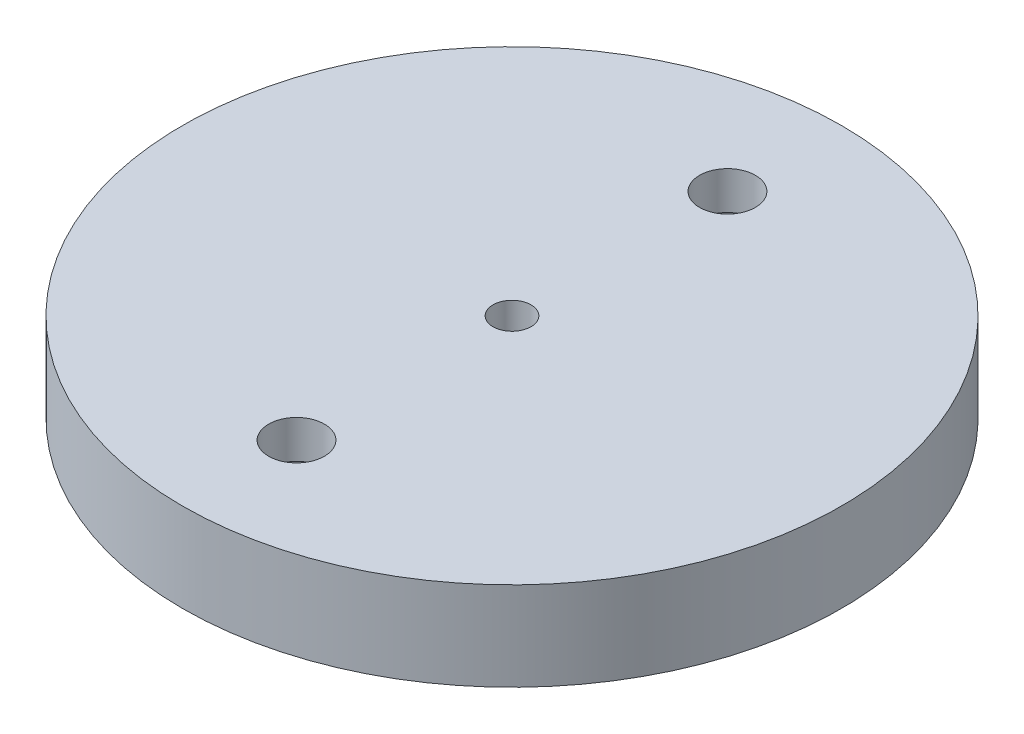
SolidWorks part; units mm, degrees
material "ABS"
ref_plane "Front Plane" through (0, 0, 0) normal (0, 0, 1) x (1, 0, 0)
ref_plane "Top Plane" through (0, 0, 0) normal (0, 1, 0) x (1, 0, 0)
ref_plane "Right Plane" through (0, 0, 0) normal (1, 0, 0) x (0, 0, -1)
sketch "Sketch1" plane through (0, 0, 0) normal (0, 1, 0) x (1, 0, 0)
  circle A0 centre (0, 0) radius 13
  circle A1 centre (0, 0) radius 1.65
  circle A2 centre (0, 8.5) radius 2.5
  circle A3 centre (0, -8.5) radius 2.5
  dimension "D1" = 26
  dimension "D2" = 3.3
  dimension "D3" = 5
  dimension "D4" = 8.5
  dimension "D5" = 8.5
extrude "Boss-Extrude1" add sketch "Sketch1" along normal blind 2
sketch "Sketch2" plane through (0, 2, 0) normal (0, 1, 0) x (1, 0, 0)
  circle A2 centre (0, 0) radius 0.75
  circle A4 centre (0, 8.5) radius 1.1
  circle A6 centre (0, 0) radius 13
  circle A7 centre (0, 0) radius 13 construction
  circle A8 centre (0, -8.5) radius 1.1
  dimension "D1" = 1.5
  dimension "D2" = 2.2
extrude "Boss-Extrude2" add sketch "Sketch2" along normal blind 1.5
